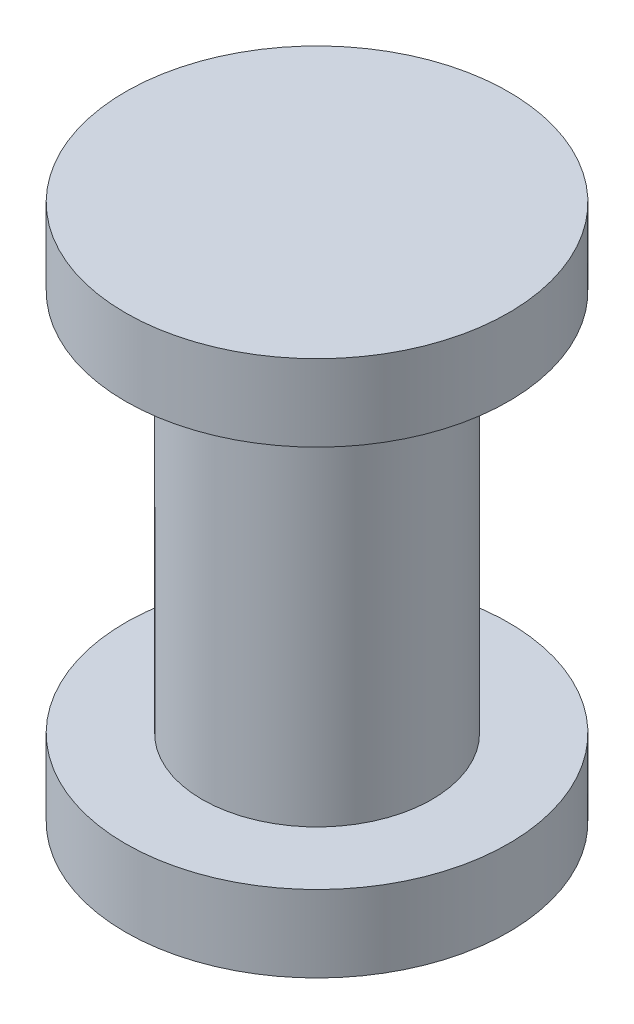
SolidWorks part; units mm, degrees
ref_plane "Front Plane" through (0, 0, 0) normal (0, 0, 1) x (1, 0, 0)
ref_plane "Top Plane" through (0, 0, 0) normal (0, 1, 0) x (1, 0, 0)
ref_plane "Right Plane" through (0, 0, 0) normal (1, 0, 0) x (0, 0, -1)
sketch "Sketch1" plane through (0, 0, 0) normal (0, 0, 1) x (1, 0, 0)
  line L0 (-14.7615, 26.9486) -> (-17.2615, 26.9486)
  line L1 (-14.7615, 26.9486) -> (-14.7615, 19.9486)
  line L2 (-14.7615, 19.9486) -> (-17.2615, 19.9486)
  line L3 (-17.2615, 19.9486) -> (-17.2615, 20.9486)
  line L4 (-17.2615, 20.9486) -> (-16.2615, 20.9486)
  line L5 (-16.2615, 20.9486) -> (-16.2615, 25.9486)
  line L6 (-16.2615, 25.9486) -> (-17.2615, 25.9486)
  line L7 (-17.2615, 25.9486) -> (-17.2615, 26.9486)
  line L8 (-14.7615, 26.9486) -> (-14.7615, 19.9486) construction
  dimension "D1" = 2.5
  dimension "D2" = 2.5
  dimension "D3" = 7
  dimension "D4" = 1.5
  dimension "D5" = 1
  dimension "D6" = 1
revolve "Revolve1" add sketch "Sketch1" angle 360 about L8
